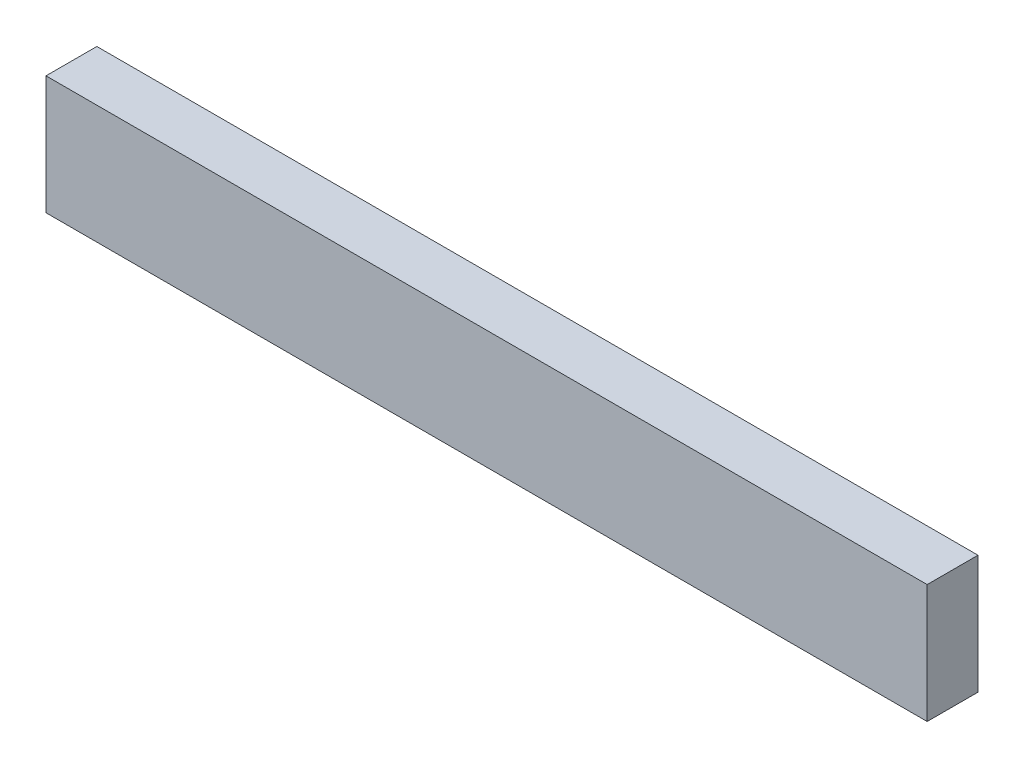
SolidWorks part; units mm, degrees
ref_plane "Front Plane" through (0, 0, 0) normal (0, 0, 1) x (1, 0, 0)
ref_plane "Top Plane" through (0, 0, 0) normal (0, 1, 0) x (1, 0, 0)
ref_plane "Right Plane" through (0, 0, 0) normal (1, 0, 0) x (0, 0, -1)
sketch "Sketch1" plane through (0, 0, 0) normal (1, 0, 0) x (0, 0, -1)
  line L1 (-19.05, -44.45) -> (19.05, -44.45)
  line L2 (-19.05, -44.45) -> (-19.05, 44.45)
  line L3 (-19.05, 44.45) -> (19.05, 44.45)
  line L4 (19.05, -44.45) -> (19.05, 44.45)
  line L5 (-19.05, -44.45) -> (19.05, 44.45) construction
  line L6 (-19.05, 44.45) -> (19.05, -44.45) construction
  point P0 (0, 0)
  dimension "D1" = 38.1
  dimension "D2" = 88.9
extrude "Boss-Extrude1" add sketch "Sketch1" along normal blind 660.4
